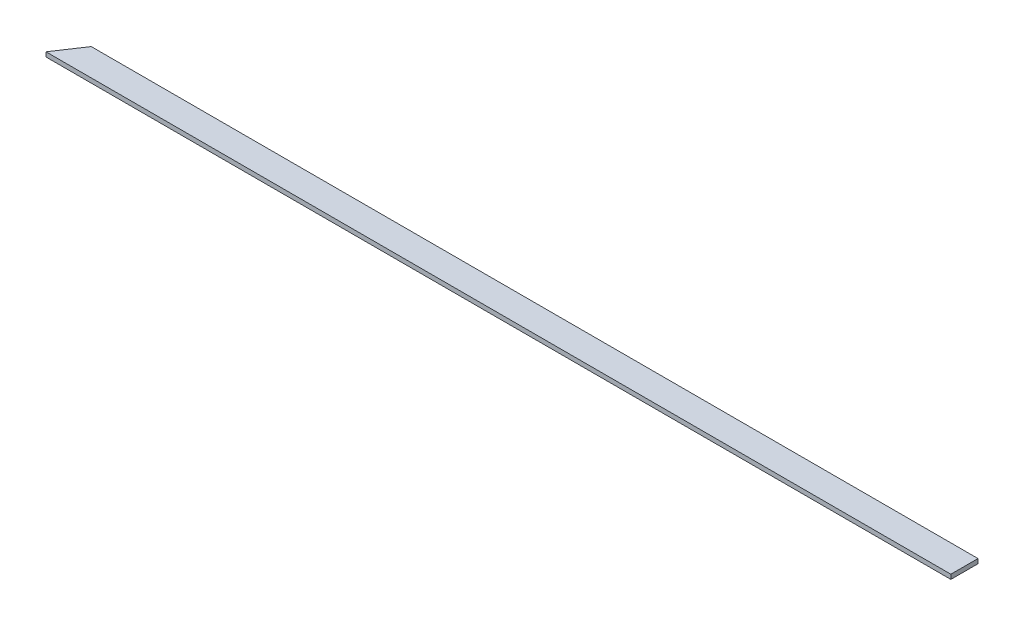
SolidWorks part; units mm, degrees
material "Epoxy, Unfilled"
ref_plane "Front Plane" through (0, 0, 0) normal (0, 0, 1) x (1, 0, 0)
ref_plane "Top Plane" through (0, 0, 0) normal (0, 1, 0) x (1, 0, 0)
ref_plane "Right Plane" through (0, 0, 0) normal (1, 0, 0) x (0, 0, -1)
sketch "Sketch1" plane through (0, 0, 0) normal (0, 1, 0) x (1, 0, 0)
  line L0 (-25, 0) -> (25, 0)
  line L1 (-25, 0) -> (-24, 1.5)
  line L2 (-24, 1.5) -> (25, 1.5)
  line L3 (25, 1.5) -> (25, 0)
  point P3 (0, 0)
  dimension "D1" = 50
  dimension "D2" = 1.5
  dimension "D3" = 1
extrude "Boss-Extrude1" add sketch "Sketch1" along normal mid plane 0.25
